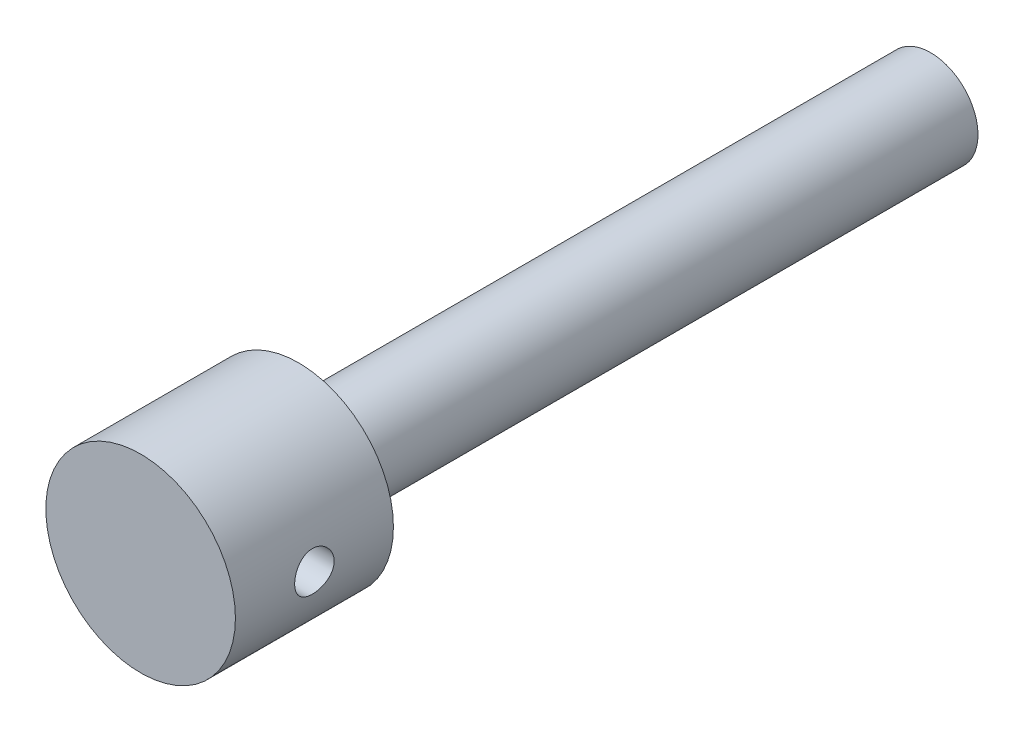
SolidWorks part; units mm, degrees
material "1060 Alloy"
ref_plane "Front Plane" through (0, 0, 0) normal (0, 0, 1) x (1, 0, 0)
ref_plane "Top Plane" through (0, 0, 0) normal (0, 1, 0) x (1, 0, 0)
ref_plane "Right Plane" through (0, 0, 0) normal (1, 0, 0) x (0, 0, -1)
sketch "Sketch1" plane through (0, 0, 0) normal (0, 0, 1) x (1, 0, 0)
  circle A0 centre (0, 0) radius 6
extrude "Boss-Extrude1" add sketch "Sketch1" along normal blind 80
sketch "Sketch2" plane through (0, 0, 80) normal (0, 0, 1) x (1, 0, 0)
  circle A0 centre (0, 0) radius 12
extrude "Boss-Extrude2" add sketch "Sketch2" along normal blind 20
ref_plane "Plane2" through (-12, 0, 0) normal (-1, 0, 0) x (0, 0, 1)
sketch "Sketch4" plane through (-12, 0, 0) normal (-1, 0, 0) x (0, 0, 1)
  line L0 (100, -12) -> (100, 12) construction
  circle A0 centre (90, 0) radius 2.5
  dimension "D1" = 10
extrude "Cut-Extrude2" cut sketch "Sketch4" against normal through all
